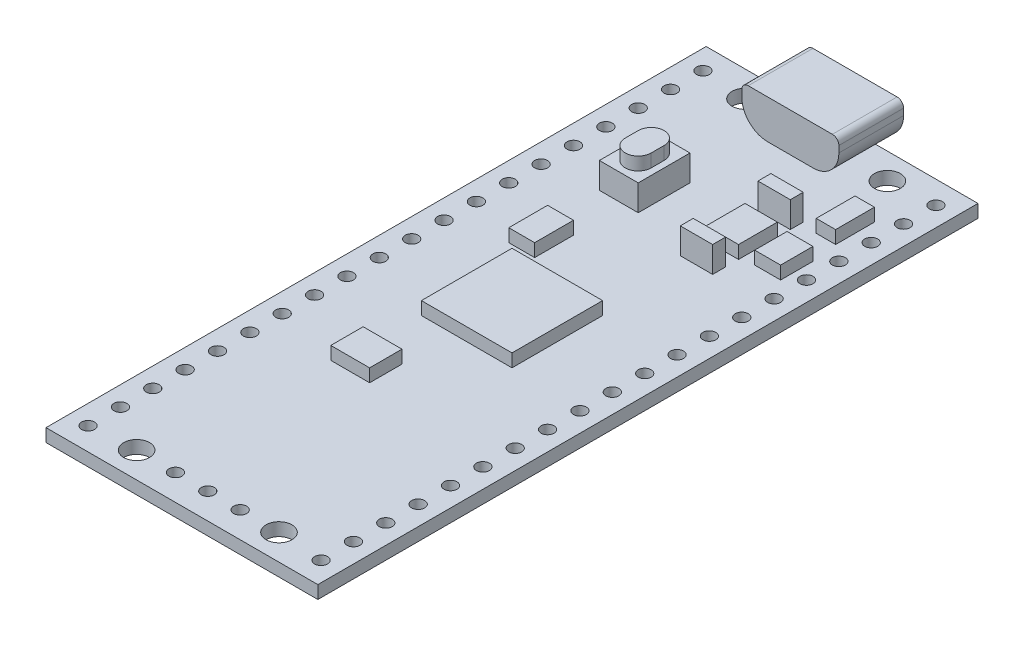
SolidWorks part; units mm, degrees
ref_plane "Front Plane" through (0, 0, 0) normal (0, 0, 1) x (1, 0, 0)
ref_plane "Top Plane" through (0, 0, 0) normal (0, 1, 0) x (1, 0, 0)
ref_plane "Right Plane" through (0, 0, 0) normal (1, 0, 0) x (0, 0, -1)
sketch "Sketch1" plane through (0, 0, 0) normal (0, 1, 0) x (1, 0, 0)
  line L1 (-10.5, 25.5) -> (10.5, 25.5)
  line L2 (-10.5, 25.5) -> (-10.5, -25.5)
  line L3 (-10.5, -25.5) -> (10.5, -25.5)
  line L4 (10.5, 25.5) -> (10.5, -25.5)
  line L5 (-10.5, 25.5) -> (10.5, -25.5) construction
  line L6 (-10.5, -25.5) -> (10.5, 25.5) construction
  point P0 (0, 0)
  dimension "D1" = 51
  dimension "D2" = 21
extrude "TopFace" add sketch "Sketch1" along normal blind 1
sketch "Sketch2" plane through (0, 1, 0) normal (0, 1, 0) x (1, 0, 0)
  line L0 (-10.5, 25.5) -> (-9, 25.5) construction
  line L1 (10.5, 25.5) -> (-10.5, 25.5) construction
  line L2 (-9, 25.5) -> (-9, -25.5) construction
  line L3 (-10.5, -25.5) -> (10.5, -25.5) construction
  line L4 (-10.5, 25.5) -> (-10.5, 23.75) construction
  line L5 (-10.5, 25.5) -> (-10.5, -25.5) construction
  line L6 (-10.5, 23.75) -> (-9, 23.75) construction
  line L7 (0, 0) -> (0, 6.7639) construction
  line L8 (10.5, 23.75) -> (9, 23.75) construction
  line L9 (10.5, 25.5) -> (10.5, 23.75) construction
  line L10 (9, 25.5) -> (9, -25.5) construction
  line L11 (10.5, 25.5) -> (9, 25.5) construction
  line L12 (0, -25.5) -> (0, -19.4824) construction
  line L13 (0, -23.5) -> (-2.5, -23.5) construction
  line L14 (0, -23.5) -> (-5.5, -23.5) construction
  line L15 (0.2689, 0) -> (5.2195, 0) construction
  circle A0 centre (-9, 23.75) radius 0.5
  circle A1 centre (-9, 21.25) radius 0.5
  circle A2 centre (-9, 18.75) radius 0.5
  circle A3 centre (-9, 16.25) radius 0.5
  circle A4 centre (-9, 13.75) radius 0.5
  circle A5 centre (-9, 11.25) radius 0.5
  circle A6 centre (-9, 8.75) radius 0.5
  circle A7 centre (-9, 6.25) radius 0.5
  circle A8 centre (-9, 3.75) radius 0.5
  circle A9 centre (-9, 1.25) radius 0.5
  circle A10 centre (-9, -1.25) radius 0.5
  circle A11 centre (-9, -3.75) radius 0.5
  circle A12 centre (-9, -6.25) radius 0.5
  circle A13 centre (-9, -8.75) radius 0.5
  circle A14 centre (-9, -11.25) radius 0.5
  circle A15 centre (-9, -13.75) radius 0.5
  circle A16 centre (-9, -16.25) radius 0.5
  circle A17 centre (-9, -18.75) radius 0.5
  circle A18 centre (-9, -21.25) radius 0.5
  circle A19 centre (-9, -23.75) radius 0.5
  circle A20 centre (9, -23.75) radius 0.5
  circle A21 centre (9, -21.25) radius 0.5
  circle A22 centre (9, -18.75) radius 0.5
  circle A23 centre (9, -16.25) radius 0.5
  circle A24 centre (9, -13.75) radius 0.5
  circle A25 centre (9, -11.25) radius 0.5
  circle A26 centre (9, -8.75) radius 0.5
  circle A27 centre (9, -6.25) radius 0.5
  circle A28 centre (9, -3.75) radius 0.5
  circle A29 centre (9, -1.25) radius 0.5
  circle A30 centre (9, 1.25) radius 0.5
  circle A31 centre (9, 3.75) radius 0.5
  circle A32 centre (9, 6.25) radius 0.5
  circle A33 centre (9, 8.75) radius 0.5
  circle A34 centre (9, 11.25) radius 0.5
  circle A35 centre (9, 13.75) radius 0.5
  circle A36 centre (9, 16.25) radius 0.5
  circle A37 centre (9, 18.75) radius 0.5
  circle A38 centre (9, 21.25) radius 0.5
  circle A39 centre (9, 23.75) radius 0.5
  circle A40 centre (0, -23.5) radius 0.5
  circle A41 centre (-2.5, -23.5) radius 0.5
  circle A42 centre (2.5, -23.5) radius 0.5
  circle A43 centre (-5.5, -23.5) radius 1
  circle A44 centre (5.5, -23.5) radius 1
  circle A45 centre (-5.5, 23.5) radius 1
  circle A46 centre (5.5, 23.5) radius 1
  dimension "D3" = 1
  dimension "D7" = 1
  dimension "D8" = 1
  dimension "D10" = 2
  dimension "D1" = 1.5
  dimension "D2" = 1.75
  dimension "D5" = 2
  dimension "D6" = 2.5
  dimension "D9" = 5.5
  dimension "D4" = 20
extrude "Cut-Extrude1" cut sketch "Sketch2" against normal through all
sketch "Sketch3" plane through (0, 1, 0) normal (0, 1, 0) x (1, 0, 0)
  line L1 (-3.5, 3.5) -> (3.5, 3.5)
  line L2 (-3.5, 3.5) -> (-3.5, -3.5)
  line L3 (-3.5, -3.5) -> (3.5, -3.5)
  line L4 (3.5, 3.5) -> (3.5, -3.5)
  line L5 (-3.5, 3.5) -> (3.5, -3.5) construction
  line L6 (-3.5, -3.5) -> (3.5, 3.5) construction
  point P0 (0, 0)
  dimension "D1" = 7
  dimension "D2" = 7
extrude "Boss-Extrude2" add sketch "Sketch3" along normal blind 1
sketch "Sketch4" plane through (0, 1, 0) normal (0, 1, 0) x (1, 0, 0)
  line L0 (-9, 13.75) -> (-2, 13.75) construction
  line L2 (-5, 15.75) -> (-2, 15.75)
  line L3 (-5, 15.75) -> (-5, 11.75)
  line L4 (-5, 11.75) -> (-2, 11.75)
  line L5 (-2, 15.75) -> (-2, 11.75)
  line L6 (-5, 15.75) -> (-2, 11.75) construction
  line L7 (-5, 11.75) -> (-2, 15.75) construction
  dimension "D1" = 7
  dimension "D2" = 3
  dimension "D3" = 4
extrude "Boss-Extrude3" add sketch "Sketch4" along normal blind 2
sketch "Sketch5" plane through (0, 3, 0) normal (0, 1, 0) x (1, 0, 0)
  line L0 (-3.5, 15.75) -> (-3.5, 11.75) construction
  line L1 (-2, 15.75) -> (-5, 15.75) construction
  line L2 (-5, 11.75) -> (-2, 11.75) construction
  line L3 (-3.5, 13.75) -> (-3.5, 14.25) construction
  line L4 (-3.5, 13.75) -> (-3.5, 13.25) construction
  line L5 (-3.5, 14.25) -> (-3.5, 13.25) construction
  line L6 (-2.5, 14.25) -> (-2.5, 13.25)
  line L7 (-4.5, 14.25) -> (-4.5, 13.25)
  arc A0 (-2.5, 14.25) -> (-4.5, 14.25) centre (-3.5, 14.25) ccw
  arc A1 (-4.5, 13.25) -> (-2.5, 13.25) centre (-3.5, 13.25) ccw
  point P8 (-3.5, 13.75)
  dimension "D2" = 1
  dimension "D1" = 0.5
  dimension "D3" = 0.5
extrude "Boss-Extrude4" add sketch "Sketch5" along normal blind 1
sketch "Sketch6" plane through (0, 1, 0) normal (0, 1, 0) x (1, 0, 0)
  line L0 (9, 18.75) -> (7, 18.75) construction
  line L1 (7, 17.25) -> (7, 14) construction
  line L2 (6.25, 20.25) -> (7.75, 20.25)
  line L3 (6.25, 20.25) -> (6.25, 17.25)
  line L4 (6.25, 17.25) -> (7.75, 17.25)
  line L5 (7.75, 20.25) -> (7.75, 17.25)
  line L6 (6.25, 20.25) -> (7.75, 17.25) construction
  line L7 (6.25, 17.25) -> (7.75, 20.25) construction
  line L8 (6, 14) -> (3.75, 14) construction
  line L9 (6, 15.25) -> (8, 15.25)
  line L10 (6, 15.25) -> (6, 12.75)
  line L11 (6, 12.75) -> (8, 12.75)
  line L12 (8, 15.25) -> (8, 12.75)
  line L13 (6, 15.25) -> (8, 12.75) construction
  line L14 (6, 12.75) -> (8, 15.25) construction
  line L15 (-9, 6.25) -> (-4, 6.25) construction
  line L16 (2.5, 15.5) -> (5, 15.5)
  line L17 (2.5, 15.5) -> (2.5, 12.5)
  line L18 (2.5, 12.5) -> (5, 12.5)
  line L19 (5, 15.5) -> (5, 12.5)
  line L20 (2.5, 15.5) -> (5, 12.5) construction
  line L21 (2.5, 12.5) -> (5, 15.5) construction
  line L22 (-9, -8.75) -> (-2.5, -8.75) construction
  line L23 (-5, 7.75) -> (-3, 7.75)
  line L24 (-5, 7.75) -> (-5, 4.75)
  line L25 (-5, 4.75) -> (-3, 4.75)
  line L26 (-3, 7.75) -> (-3, 4.75)
  line L27 (-5, 7.75) -> (-3, 4.75) construction
  line L28 (-5, 4.75) -> (-3, 7.75) construction
  line L30 (-4, -7.5) -> (-1, -7.5)
  line L31 (-4, -7.5) -> (-4, -10)
  line L32 (-4, -10) -> (-1, -10)
  line L33 (-1, -7.5) -> (-1, -10)
  line L34 (-4, -7.5) -> (-1, -10) construction
  line L35 (-4, -10) -> (-1, -7.5) construction
  dimension "D1" = 2
  dimension "D2" = 1.5
  dimension "D3" = 3
  dimension "D4" = 3.25
  dimension "D5" = 2
  dimension "D6" = 2.5
  dimension "D7" = 2.25
  dimension "D8" = 2.5
  dimension "D9" = 3
  dimension "D10" = 5
  dimension "D11" = 2
  dimension "D12" = 3
  dimension "D13" = 6.5
  dimension "D14" = 3
  dimension "D15" = 2.5
extrude "Boss-Extrude5" add sketch "Sketch6" along normal blind 1
sketch "Sketch7" plane through (0, 1, 0) normal (0, 1, 0) x (1, 0, 0)
  line L0 (3.75, 15.5) -> (3.75, 12.5) construction
  line L1 (5, 15.5) -> (2.5, 15.5) construction
  line L2 (2.5, 12.5) -> (5, 12.5) construction
  line L3 (3.75, 17) -> (3.75, 11) construction
  line L5 (3.75, 14) -> (-0.486, 14) construction
  line L6 (2.5, 17.5) -> (5, 17.5)
  line L7 (2.5, 17.5) -> (2.5, 16.5)
  line L8 (2.5, 16.5) -> (5, 16.5)
  line L9 (5, 17.5) -> (5, 16.5)
  line L10 (2.5, 17.5) -> (5, 16.5) construction
  line L11 (2.5, 16.5) -> (5, 17.5) construction
  line L12 (5, 10.5) -> (5, 11.5)
  line L13 (2.5, 11.5) -> (5, 11.5)
  line L14 (2.5, 10.5) -> (2.5, 11.5)
  line L15 (2.5, 10.5) -> (5, 10.5)
  point P9 (3.75, 14)
  dimension "D1" = 6
  dimension "D2" = 1
  dimension "D3" = 2.5
extrude "Boss-Extrude6" add sketch "Sketch7" along normal blind 2
sketch "Sketch8" plane through (0, 0, -25.5) normal (0, 0, -1) x (-1, 0, 0)
  line L0 (0, 1) -> (0, 4) construction
  line L1 (-3.5, 1) -> (3.5, 1) construction
  line L2 (2, 1) -> (5, 1) construction
  line L3 (-3.25, 4) -> (3.25, 4)
  line L4 (-3.75, 3.5) -> (-3.75, 3)
  line L5 (-1.75, 1) -> (1.75, 1)
  line L6 (3.75, 3.5) -> (3.75, 3)
  line L7 (-3.75, 4) -> (3.75, 1) construction
  line L8 (-3.75, 1) -> (3.75, 4) construction
  arc A0 (3.25, 4) -> (3.75, 3.5) centre (3.25, 3.5) cw
  arc A1 (-3.25, 4) -> (-3.75, 3.5) centre (-3.25, 3.5) ccw
  arc A2 (1.75, 1) -> (3.75, 3) centre (1.75, 3) ccw
  arc A3 (-1.75, 1) -> (-3.75, 3) centre (-1.75, 3) cw
  point P5 (0, 2.5)
  dimension "D3" = 0.5
  dimension "D4" = 2
  dimension "D1" = 3
  dimension "D2" = 7.5
extrude "Boss-Extrude7" add sketch "Sketch8" against normal blind 4
sketch "Sketch9" plane through (0, 0, -25.5) normal (0, 0, -1) x (-1, 0, 0)
  line L0 (-1.75, 1) -> (1.75, 1)
  line L8 (-10.5, 0) -> (10.5, 0)
  line L9 (10.5, 0) -> (10.5, 1)
  line L10 (10.5, 1) -> (1.75, 1)
  line L11 (3.75, 3) -> (3.75, 3.5)
  line L12 (3.25, 4) -> (-3.25, 4)
  line L13 (-3.75, 3.5) -> (-3.75, 3)
  line L14 (-1.75, 1) -> (-10.5, 1)
  line L15 (-10.5, 1) -> (-10.5, 0)
  line L19 (3.75, 3) -> (3.75, 3.5)
  line L20 (3.25, 4) -> (-3.25, 4)
  line L21 (-3.75, 3.5) -> (-3.75, 3)
  arc A4 (1.75, 1) -> (3.75, 3) centre (1.75, 3) ccw
  arc A5 (3.75, 3.5) -> (3.25, 4) centre (3.25, 3.5) ccw
  arc A6 (-3.25, 4) -> (-3.75, 3.5) centre (-3.25, 3.5) ccw
  arc A7 (-3.75, 3) -> (-1.75, 1) centre (-1.75, 3) ccw
  arc A8 (1.75, 1) -> (3.75, 3) centre (1.75, 3) ccw
  arc A9 (3.75, 3.5) -> (3.25, 4) centre (3.25, 3.5) ccw
  arc A10 (-3.25, 4) -> (-3.75, 3.5) centre (-3.25, 3.5) ccw
  arc A11 (-3.75, 3) -> (-1.75, 1) centre (-1.75, 3) ccw
  dimension "D1" = 0
extrude "Boss-Extrude8" add sketch "Sketch9" along normal blind 1
sketch "Sketch10" plane through (0, 0, -26.5) normal (0, 0, -1) x (-1, 0, 0)
  line L0 (3.25, 3.9) -> (-3.25, 3.9)
  line L1 (-3.65, 3.5) -> (-3.65, 3)
  line L2 (-1.75, 1.1) -> (1.75, 1.1)
  line L3 (3.65, 3) -> (3.65, 3.5)
  line L4 (3.75, 3) -> (3.75, 3.5)
  line L5 (3.25, 4) -> (-3.25, 4)
  line L6 (-3.75, 3.5) -> (-3.75, 3)
  line L7 (-1.75, 1) -> (1.75, 1)
  line L8 (3.75, 3) -> (3.75, 3.5)
  line L9 (3.25, 4) -> (-3.25, 4)
  line L10 (-3.75, 3.5) -> (-3.75, 3)
  line L11 (-1.75, 1) -> (1.75, 1)
  arc A0 (-3.25, 3.9) -> (-3.65, 3.5) centre (-3.25, 3.5) ccw
  arc A1 (-3.65, 3) -> (-1.75, 1.1) centre (-1.75, 3) ccw
  arc A2 (1.75, 1.1) -> (3.65, 3) centre (1.75, 3) ccw
  arc A3 (3.65, 3.5) -> (3.25, 3.9) centre (3.25, 3.5) ccw
  arc A4 (1.75, 1) -> (3.75, 3) centre (1.75, 3) ccw
  arc A5 (3.75, 3.5) -> (3.25, 4) centre (3.25, 3.5) ccw
  arc A6 (-3.25, 4) -> (-3.75, 3.5) centre (-3.25, 3.5) ccw
  arc A7 (-3.75, 3) -> (-1.75, 1) centre (-1.75, 3) ccw
  arc A8 (1.75, 1) -> (3.75, 3) centre (1.75, 3) ccw
  arc A9 (3.75, 3.5) -> (3.25, 4) centre (3.25, 3.5) ccw
  arc A10 (-3.25, 4) -> (-3.75, 3.5) centre (-3.25, 3.5) ccw
  arc A11 (-3.75, 3) -> (-1.75, 1) centre (-1.75, 3) ccw
  dimension "D1" = 0
  dimension "D2" = 0.1
extrude "Cut-Extrude2" cut sketch "Sketch10" against normal blind 4.8 contours L0 A0 L1 A1 L2 A2 L3 A3
sketch "Sketch11" plane through (0, 0, -21.7) normal (0, 0, -1) x (-1, 0, 0)
  line L0 (0, 3.9) -> (0, 3.15) construction
  line L1 (3.25, 3.9) -> (-3.25, 3.9) construction
  line L3 (-1.5, 3.25) -> (1.5, 3.25)
  line L4 (-1.5, 3.25) -> (-1.5, 3.05)
  line L5 (-1.5, 3.05) -> (1.5, 3.05)
  line L6 (1.5, 3.25) -> (1.5, 3.05)
  line L7 (-1.5, 3.25) -> (1.5, 3.05) construction
  line L8 (-1.5, 3.05) -> (1.5, 3.25) construction
  dimension "D1" = 0.75
  dimension "D2" = 0.2
  dimension "D3" = 3
extrude "Boss-Extrude9" add sketch "Sketch11" along normal blind 3
